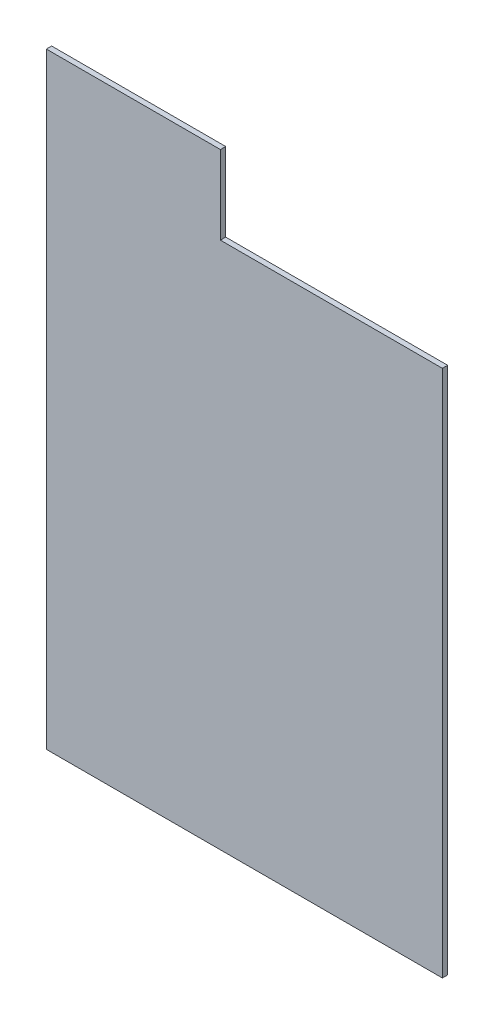
SolidWorks part; units mm, degrees
ref_plane "Front Plane" through (0, 0, 0) normal (0, 0, 1) x (1, 0, 0)
ref_plane "Top Plane" through (0, 0, 0) normal (0, 1, 0) x (1, 0, 0)
ref_plane "Right Plane" through (0, 0, 0) normal (1, 0, 0) x (0, 0, -1)
sketch "Sketch1" plane through (0, 0, 0) normal (0, 0, 1) x (1, 0, 0)
  line L0 (0, 100) -> (0, 114.8639)
  line L1 (0, 0) -> (75, 0)
  line L2 (0, 0) -> (0, 100)
  line L3 (32.9665, 100) -> (75, 100)
  line L4 (75, 0) -> (75, 100)
  line L5 (0, 114.8639) -> (32.9665, 114.8639)
  line L6 (32.9665, 114.8639) -> (32.9665, 100)
  dimension "D1" = 100
  dimension "D2" = 75
extrude "Boss-Extrude1" add sketch "Sketch1" along normal blind 1
